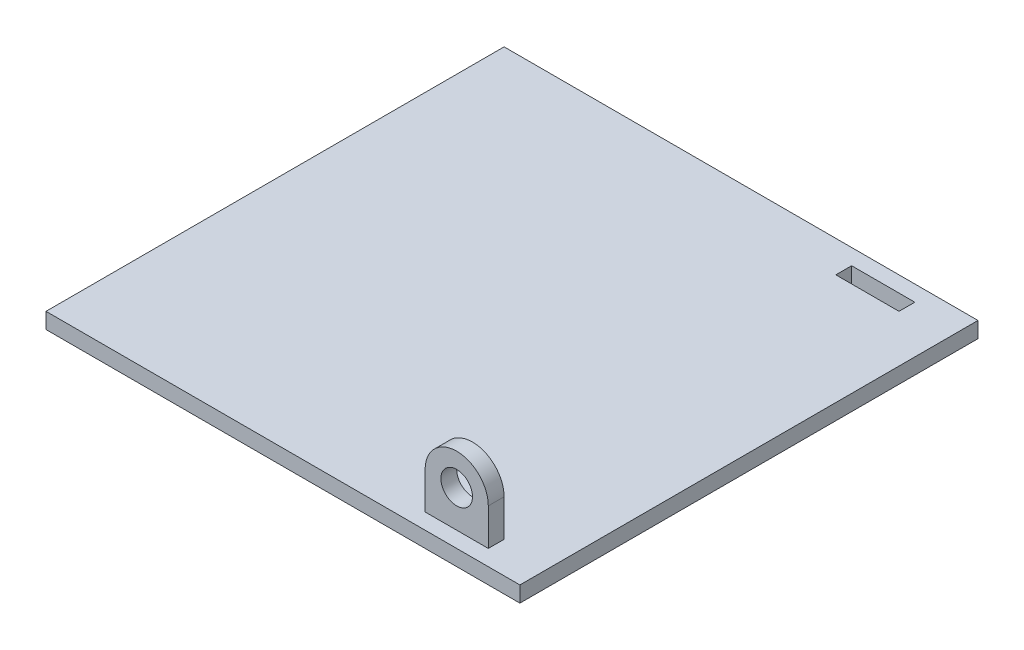
SolidWorks part; units mm, degrees
material "ABS"
ref_plane "Front Plane" through (0, 0, 0) normal (0, 0, 1) x (1, 0, 0)
ref_plane "Top Plane" through (0, 0, 0) normal (0, 1, 0) x (1, 0, 0)
ref_plane "Right Plane" through (0, 0, 0) normal (1, 0, 0) x (0, 0, -1)
sketch "Sketch1" plane through (0, 0, 0) normal (0, 1, 0) x (1, 0, 0)
  line L1 (-45, -43.5) -> (45, -43.5)
  line L2 (-45, -43.5) -> (-45, 43.5)
  line L3 (-45, 43.5) -> (45, 43.5)
  line L4 (45, -43.5) -> (45, 43.5)
  line L5 (-45, -43.5) -> (45, 43.5) construction
  line L6 (-45, 43.5) -> (45, -43.5) construction
  line L7 (24, 40.5) -> (36, 40.5)
  line L8 (24, 40.5) -> (24, 37.5)
  line L9 (24, 37.5) -> (36, 37.5)
  line L10 (36, 40.5) -> (36, 37.5)
  line L11 (24, 40.5) -> (36, 37.5) construction
  line L12 (24, 37.5) -> (36, 40.5) construction
  point P0 (0, 0)
  point P10 (30, 39)
  dimension "D1" = 90
  dimension "D2" = 87
  dimension "D3" = 3
  dimension "D4" = 12
  dimension "D5" = 15
  dimension "D6" = 3
extrude "Boss-Extrude1" add sketch "Sketch1" along normal blind 3
ref_plane "Plane1" through (0, 0, 40.5) normal (0, 0, 1) x (1, 0, 0)
sketch "Sketch3" plane through (0, 0, 40.5) normal (0, 0, 1) x (1, 0, 0)
  line L0 (24, 3) -> (24, 10)
  line L1 (36, 3) -> (36, 10)
  line L2 (24, 3) -> (36, 10) construction
  line L3 (24, 10) -> (36, 3) construction
  line L4 (24, 3) -> (36, 3)
  line L5 (-45, 3) -> (45, 3) construction
  line L6 (45, 3) -> (45, 0) construction
  arc A0 (24, 10) -> (36, 10) centre (30, 10) cw
  circle A1 centre (30, 10) radius 3
  point P4 (30, 6.5)
  dimension "D1" = 6
  dimension "D3" = 6
  dimension "D2" = 7
  dimension "D4" = 15
extrude "Boss-Extrude2" add sketch "Sketch3" against normal blind 3
